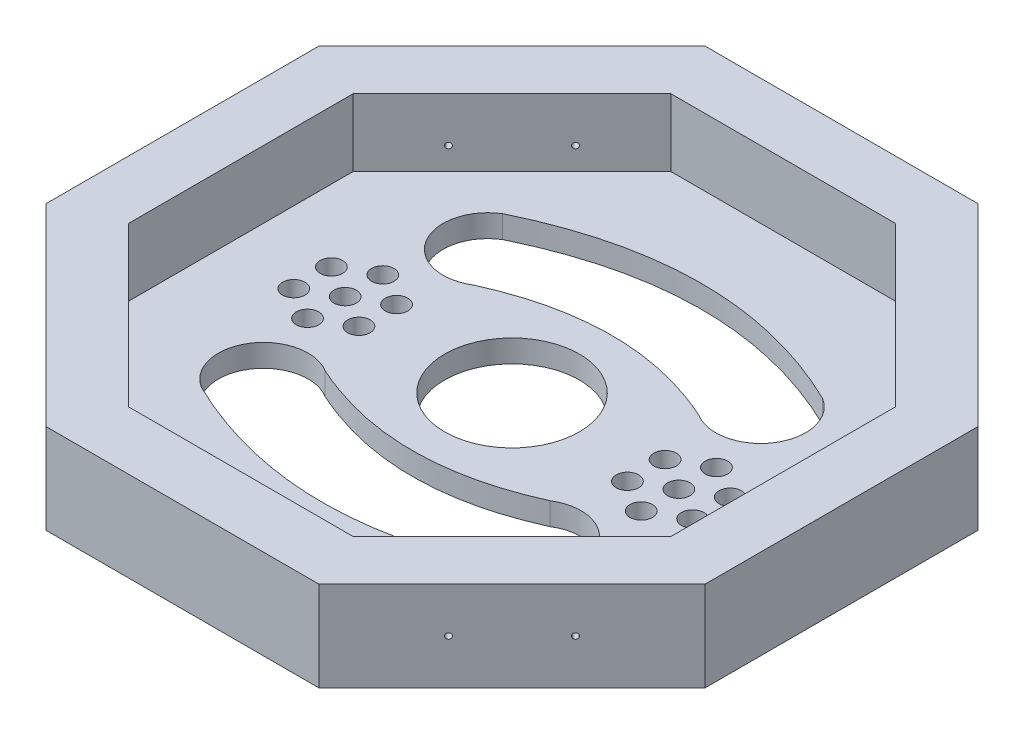
SolidWorks part; units mm, degrees
ref_plane "Plano frontal" through (0, 0, 0) normal (0, 0, 1) x (1, 0, 0)
ref_plane "Plano superior" through (0, 0, 0) normal (0, 1, 0) x (1, 0, 0)
ref_plane "Plano direito" through (0, 0, 0) normal (1, 0, 0) x (0, 0, -1)
sketch "Esboço1" plane through (0, 0, 0) normal (0, 1, 0) x (1, 0, 0)
  line L24 (146.6822, -60.7578) -> (146.6822, 60.7578)
  line L37 (60.7578, 146.6822) -> (-60.7578, 146.6822)
  line L38 (-60.7578, 146.6822) -> (-146.6822, 60.7578)
  line L39 (-146.6822, 60.7578) -> (-146.6822, -60.7578)
  line L40 (-146.6822, -60.7578) -> (-60.7578, -146.6822)
  line L41 (-60.7578, -146.6822) -> (60.7578, -146.6822)
  line L42 (60.7578, -146.6822) -> (146.6822, -60.7578)
  line L43 (146.6822, 60.7578) -> (60.7578, 146.6822)
  circle A0 centre (0, 0) radius 146.6822 construction
  point P1 (-146.6822, 0)
extrude "Ressalto-extrusão1" add sketch "Esboço1" along normal blind 40
sketch "Esboço2" plane through (0, 40, 0) normal (0, 1, 0) x (1, 0, 0)
  line L1 (120.7107, 50) -> (50, 120.7107)
  line L2 (50, 120.7107) -> (-50, 120.7107)
  line L3 (-50, 120.7107) -> (-120.7107, 50)
  line L4 (-120.7107, 50) -> (-120.7107, -50)
  line L5 (-120.7107, -50) -> (-50, -120.7107)
  line L6 (-50, -120.7107) -> (50, -120.7107)
  line L7 (50, -120.7107) -> (120.7107, -50)
  line L8 (120.7107, -50) -> (120.7107, 50)
  circle A0 centre (0, 0) radius 120.7107 construction
  point P1 (-120.7107, 0)
  dimension "D1" = 100
extrude "Corte-extrusão2" cut sketch "Esboço2" against normal blind 25 from offset 5 offset against normal yes
sketch "Esboço3" plane through (0, 40, 0) normal (0, 1, 0) x (1, 0, 0)
  line L1 (120.7107, 50) -> (50, 120.7107)
  line L2 (50, 120.7107) -> (-50, 120.7107)
  line L3 (-50, 120.7107) -> (-120.7107, 50)
  line L4 (-120.7107, 50) -> (-120.7107, -50)
  line L5 (-120.7107, -50) -> (-50, -120.7107)
  line L6 (-50, -120.7107) -> (50, -120.7107)
  line L7 (50, -120.7107) -> (120.7107, -50)
  line L8 (120.7107, -50) -> (120.7107, 50)
  circle A0 centre (0, 0) radius 120.7107 construction
  point P12 (-120.7107, 0)
  dimension "D1" = 100
extrude "Corte-extrusão3" cut sketch "Esboço3" against normal blind 25
sketch "Esboço4" plane through (0, 10, 0) normal (0, 1, 0) x (1, 0, 0)
  line L0 (-120.7107, 50) -> (-60.7107, 50) construction
  line L1 (-120.7107, 50) -> (-120.7107, -50) construction
  line L2 (0, -22) -> (0, 22) construction
  line L3 (0, 84.404) -> (0, 44.404) construction
  line L4 (-22, 0) -> (22, 0) construction
  circle A0 centre (0, 0) radius 30
  arc A1 (-71.1731, 67.0452) -> (-50.0817, 33.0582) centre (-60.7107, 50) ccw
  arc A5 (71.1731, 67.0452) -> (50.0817, 33.0582) centre (60.7107, 50) cw
  arc A6 (-71.1731, -67.0452) -> (-50.0817, -33.0582) centre (-60.7107, -50) cw
  arc A7 (71.1731, -67.0452) -> (50.0817, -33.0582) centre (60.7107, -50) ccw
  circle A11 centre (-74.2664, 16.749) radius 5
  circle A13 centre (-59.7613, 8.3745) radius 5
  circle A14 centre (-59.7613, -8.3745) radius 5
  circle A15 centre (-74.2664, -16.749) radius 5
  circle A16 centre (-88.7715, -8.3745) radius 5
  circle A17 centre (-88.7715, 8.3745) radius 5
  circle A18 centre (-74.2664, 0) radius 5
  circle A19 centre (74.2664, 0) radius 5
  circle A20 centre (88.7715, 8.3745) radius 5
  circle A21 centre (88.7715, -8.3745) radius 5
  circle A22 centre (74.2664, -16.749) radius 5
  circle A23 centre (59.7613, -8.3745) radius 5
  circle A24 centre (59.7613, 8.3745) radius 5
  circle A25 centre (74.2664, 16.749) radius 5
  spline S0 degree 2 poles (-71.1731, 67.0452) (0, 101.7629) (71.1731, 67.0452) knots 0 0 0 1 1 1
  spline S1 degree 2 poles (-50.0817, 33.0582) (0, 55.7499) (50.0817, 33.0582) knots 0 0 0 1 1 1
  spline S2 degree 2 poles (-71.1731, -67.0452) (0, -101.7629) (71.1731, -67.0452) knots 0 0 0 1 1 1
  spline S3 degree 2 poles (-50.0817, -33.0582) (0, -55.7499) (50.0817, -33.0582) knots 0 0 0 1 1 1
  point P46 (-74.2664, 0)
  point P58 (74.2664, 0)
  dimension "D1" = 40
  dimension "D5" = 60
  dimension "D6" = 10
  dimension "D2" = 90
  dimension "D3" = 60
  dimension "D4" = 40
  dimension "D7" = 6
extrude "Corte-extrusão4" cut sketch "Esboço4" against normal blind 10
hole_wizard "Broca de rosquear para tarraxa de M31" positions "Esboço7" profile "Esboço8" hole size "M3" standard "ISO" end condition through all
sketch "Esboço7" plane through (103.72, 0, 103.72) normal (0.7071, 0, 0.7071) x (0.7071, 0, -0.7071)
  line L0 (-20, 20) -> (20, 20) construction
  line L1 (-60.7578, 0) -> (60.7578, 0) construction
  point P0 (-20, 20)
  point P2 (20, 20)
  point P8 (0, 20)
  dimension "D1" = 40
  dimension "D2" = 20
sketch "Esboço8" plane through (89.5778, 20, 117.8621) normal (0, 1, 0) x (0.7071, 0, -0.7071)
  line L0 (0, 0) -> (0, 354.1222)
  line L1 (0, 354.1222) -> (1.25, 354.1222)
  line L2 (1.25, 354.1222) -> (1.25, 0)
  line L5 (1.25, 0) -> (0, 0)
  line L11 (0, -6.35) -> (0, 107.95) construction
  dimension "Thru Hole Dia." = 2.5
  dimension "Thru Hole Depth" = 354.1222
hole_wizard "Broca de rosquear para tarraxa de M32" positions "Esboço9" profile "Esboço10" hole size "M3" standard "ISO" end condition through all
sketch "Esboço9" plane through (-103.72, 0, 103.72) normal (-0.7071, 0, 0.7071) x (0.7071, 0, 0.7071)
  line L0 (-20, 20) -> (20, 20) construction
  line L2 (-60.7578, 0) -> (60.7578, 0) construction
  point P0 (-20, 20)
  point P2 (20, 20)
  point P9 (0, 20)
  dimension "D1" = 20
  dimension "D2" = 40
sketch "Esboço10" plane through (-117.8621, 20, 89.5778) normal (0, 1, 0) x (0.7071, 0, 0.7071)
  line L0 (0, 0) -> (0, 354.1222)
  line L1 (0, 354.1222) -> (1.25, 354.1222)
  line L2 (1.25, 354.1222) -> (1.25, 0)
  line L5 (1.25, 0) -> (0, 0)
  line L11 (0, -6.35) -> (0, 107.95) construction
  dimension "Thru Hole Dia." = 2.5
  dimension "Thru Hole Depth" = 354.1222
